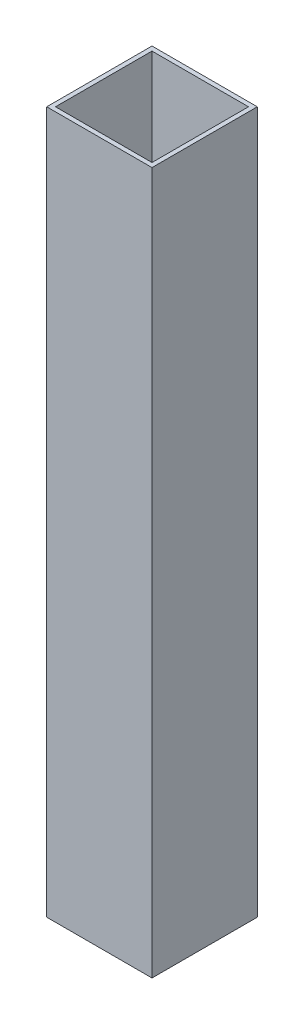
SolidWorks part; units mm, degrees
ref_plane "Front Plane" through (0, 0, 0) normal (0, 0, 1) x (1, 0, 0)
ref_plane "Top Plane" through (0, 0, 0) normal (0, 1, 0) x (1, 0, 0)
ref_plane "Right Plane" through (0, 0, 0) normal (1, 0, 0) x (0, 0, -1)
other "Configuration Table"
sketch "Sketch1" plane through (0, 0, 0) normal (0, 1, 0) x (1, 0, 0)
  line L1 (19.05, 19.05) -> (-19.05, 19.05)
  line L2 (19.05, 19.05) -> (19.05, -19.05)
  line L3 (19.05, -19.05) -> (-19.05, -19.05)
  line L4 (-19.05, 19.05) -> (-19.05, -19.05)
  line L5 (19.05, 19.05) -> (-19.05, -19.05) construction
  line L6 (19.05, -19.05) -> (-19.05, 19.05) construction
  line L7 (17.4625, -17.4625) -> (-17.4625, -17.4625)
  line L8 (17.4625, -17.4625) -> (17.4625, 17.4625)
  line L9 (17.4625, 17.4625) -> (-17.4625, 17.4625)
  line L10 (-17.4625, -17.4625) -> (-17.4625, 17.4625)
  line L11 (17.4625, -17.4625) -> (-17.4625, 17.4625) construction
  line L12 (17.4625, 17.4625) -> (-17.4625, -17.4625) construction
  point P0 (0, 0)
  point P6 (0, 0)
  dimension "D1" = 38.1
  dimension "D2" = 1.5875
extrude "Boss-Extrude1" add sketch "Sketch1" along normal blind 254
